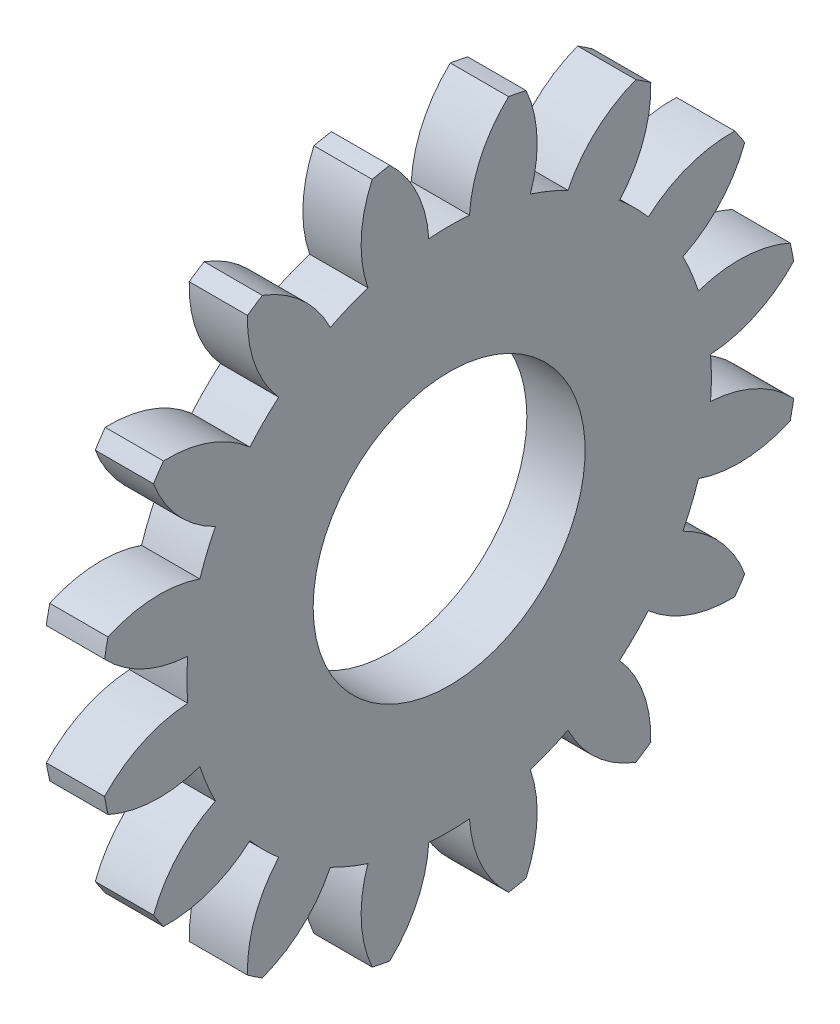
SolidWorks part; units mm, degrees
material "Zinc AC41A Alloy, As Cast"
ref_plane "Plane1" through (0, 0, 0) normal (0, 0, 1) x (1, 0, 0)
ref_plane "Plane2" through (0, 0, 0) normal (0, 1, 0) x (1, 0, 0)
ref_plane "Plane3" through (0, 0, 0) normal (1, 0, 0) x (0, 0, -1)
sketch "HoldingSke" plane through (0, 0, 0) normal (0, 1, 0) x (1, 0, 0)
  line L0 (0, 0) -> (0.9613, -0.2756)
  line L1 (-15, 0) -> (100, 0) construction
  line L2 (0, 0) -> (-2.1039, 2.3779)
  line L3 (0, 0) -> (-11.863, 4.5341)
  line L4 (0, 0) -> (8.3015, 2.3804)
  line L5 (0, 0) -> (-46.8476, -17.4728)
  line L6 (0, 0) -> (-1.2434, -0.839)
  line L7 (-2.1039, 2.3779) -> (8.6586, 51.2059)
  line L8 (-76.2, 54.61) -> (-75.2, 54.61)
  line L9 (-71.009, 38.7566) -> (-53.1078, 45.2721)
  line L10 (-76.2, 71.12) -> (104.1128, 71.12)
  line L11 (0, 0) -> (-1.5, 0)
  line L12 (-76.2, 101.6) -> (-76.162, 101.6)
  line L13 (24.9733, 27.94) -> (52.9518, 28.4284)
  line L14 (24.9733, 27.94) -> (24.9743, 27.94)
  line L15 (24.9733, 27.94) -> (100.4006, 29.5858)
  line L16 (-63.627, -1) -> (-12.827, -1)
  circle A0 centre (0, 0) radius 3.5
  circle A1 centre (0, 0) radius 6.749
  circle A2 centre (0, 0) radius 37.5
  circle A3 centre (0, 0) radius 3.5
  dimension "MHD" = 13.498
  dimension "Hub_dia" = 75
  dimension "Bore" = 7
  dimension "MBD" = 7
  dimension "Num_teeth" = 16
  dimension "Pitch" = 1
  dimension "Overall_len" = 50
  dimension "Show_teeth" = 16
  dimension "Thickness" = 1.5
  dimension "OAL" = 50.0001
  dimension "T_dim" = 1
  dimension "Ap" = 20
  dimension "H" = 19.05
  dimension "Pitch_radius" = 180.3128
  dimension "Width" = 1.5
  dimension "Backlash" = 0.038
  dimension "Addendum_fac" = 1
  dimension "Dedendum_fac" = 1.25
  dimension "Clearance_fac" = 0.25
  dimension "Dedendum_add" = 0.001
  dimension "Module" = 1
sketch "BasProSke" plane through (0, 0, 0) normal (0, 1, 0) x (1, 0, 0)
  line L0 (-10, 0) -> (60, 0) construction
  line L1 (0, 0) -> (0, 9)
  line L2 (0, 0) -> (1.5, 0)
  line L3 (1.5, 0) -> (1.5, 9)
  line L4 (1.5, 9) -> (0, 9)
  dimension "Thickness" = 1.5
  dimension "Diameter" = 18
revolve "Base-Revolve" add sketch "BasProSke" angle 360 about L0
sketch "TooCutSke" plane through (0, 0, 0) normal (1, 0, 0) x (0, 0, -1)
  line L1 (0, 0) -> (0, 107) construction
  line L2 (0, 0) -> (-0.8506, 7.9547) construction
  line L3 (0, 0) -> (-3.1089, 15.6293) construction
  line L4 (-0.8506, 7.9547) -> (-1.5544, 7.8146) construction
  arc A0 (0.5238, 6.7286) -> (-0.5238, 6.7286) centre (0, 0) ccw
  arc A1 (1.5534, 8.8907) -> (-1.5534, 8.8907) centre (0, 0) ccw
  circle A2 centre (0, 0) radius 8 construction
  circle A3 centre (0, 0) radius 7.5175 construction
  arc A4 (-0.5238, 6.7286) -> (-1.5534, 8.8907) centre (-3.7179, 6.5338) ccw
  arc A5 (1.5534, 8.8907) -> (0.5238, 6.7286) centre (3.7179, 6.5338) ccw
  dimension "Root_dia" = 13.498
  dimension "Overcut_dia" = 18.0508
  dimension "Pitch_dia" = 16
  dimension "Base_dia" = 15.0351
  dimension "Flank_rad" = 3.2
  dimension "Half_ang" = 11.25
  dimension "Half_CT" = 0.7176
extrude "ToothCut" cut sketch "TooCutSke" along normal through all
fillet "Breaks" [suppressed] radius 0.02
fillet "RootFillets" [suppressed] radius 0.251
pattern_circular "TeethCuts" count 16 every 22.5 about axis through (-10, 0, 0) along (1, 0, 0) of "ToothCut", "RootFillets", "Breaks"
sketch "HubNeaOneSke" plane through (0, 0, 0) normal (-1, 0, 0) x (0, 0, 1)
  circle A0 centre (0, 0) radius 6.749
  dimension "Diameter" = 13.498
extrude "HubNearOne" [suppressed] add sketch "HubNeaOneSke" along normal blind 48.5001
sketch "HubNeaBotSke" plane through (0, 0, 0) normal (-1, 0, 0) x (0, 0, 1)
  circle A0 centre (0, 0) radius 6.749
  dimension "Diameter" = 13.498
extrude "HubNearBoth" [suppressed] add sketch "HubNeaBotSke" along normal blind 24.25
ref_plane "FarPln" through (1.5, 0, 0) normal (1, 0, 0) x (0, 0, -1)
sketch "HubFarSke" plane through (1.5, 0, 0) normal (1, 0, 0) x (0, 0, -1)
  circle A0 centre (0, 0) radius 6.749
  dimension "Diameter" = 13.498
extrude "HubFar" [suppressed] add sketch "HubFarSke" along normal blind 24.25
sketch "BorSke" plane through (0, 0, 0) normal (1, 0, 0) x (0, 0, -1)
  circle A0 centre (0, 0) radius 3.5
  dimension "Diameter" = 7
extrude "Bore" cut sketch "BorSke" along normal mid plane 100.0001
sketch "KeySke" plane through (0, 0, 0) normal (1, 0, 0) x (0, 0, -1)
  line L0 (-1, 0) -> (-1, 4.5)
  line L1 (-1, 4.5) -> (1, 4.5)
  line L2 (1, 4.5) -> (1, 0)
  line L3 (0, 0) -> (0, 34) construction
  line L4 (-1, 0) -> (1, 0)
  dimension "Offset" = 4.5
  dimension "Width" = 2
extrude "Keyway" [suppressed] cut sketch "KeySke" along normal mid plane 100.0001
pattern_circular "Keyway2" [suppressed] count 2 every 90 about axis through (-10, 0, 0) along (1, 0, 0)
equation "' \"Module@HoldingSke\" = 6.35"
equation "' \"Num_teeth@HoldingSke\" = 12"
equation "' \"Ap@HoldingSke\" =  20"
equation "' \"Ap@HoldingSke\" = 20"
equation "' \"Width@HoldingSke\" = 0.5 * 25.4"
equation "' \"Hub_dia@HoldingSke\"= 1 * 25.4"
equation "' \"Hub_dia@HoldingSke\" = 1 * 25.4"
equation "' \"Overall_len@HoldingSke\" = 1.0 * 25.4"
equation "' \"Bore@HoldingSke\" = 0.75 * 25.4"
equation "' \"T_dim@HoldingSke\" = 0.1 * 25.4"
equation "' \"Width@KeySke\" = 0.25 * 25.4"
equation "' \"Show_teeth@HoldingSke\" = 13"
equation "' \"Backlash@HoldingSke\" = 0.009 * 25.4"
equation "' \"Addendum_fac@HoldingSke\" = 1.0"
equation "' \"Dedendum_fac@HoldingSke\" = 1.25"
equation "' \"Dedendum_add@HoldingSke\" = 0.00005 * 25.4"
equation "' \"Clearance_fac@HoldingSke\" = 0.25"
equation "\"Pitch@HoldingSke\" = 1 / \"Module@HoldingSke\""
equation "\"Overcut_dia@TooCutSke\" = (\"Num_teeth@HoldingSke\" + 2 * \"Addendum_fac@HoldingSke\") / \"Pitch@HoldingSke\" + 0.002 * 25.4"
equation "\"Pitch_dia@TooCutSke\" = \"Num_teeth@HoldingSke\" / \"Pitch@HoldingSke\""
equation "\"Base_dia@TooCutSke\" = \"Num_teeth@HoldingSke\" / \"Pitch@HoldingSke\" * cos((\"Ap@HoldingSke\"  * 3.14159265 / 180))"
equation "\"Root_dia@TooCutSke\" = (\"Num_teeth@HoldingSke\" + 2) / \"Pitch@HoldingSke\" - 2 * (\"Addendum_fac@HoldingSke\" + \"Dedendum_fac@HoldingSke\") / \"Pitch@HoldingSke\" - \"Dedendum_add@HoldingSke\" * 2"
equation "\"Half_ang@TooCutSke\" = 180 / \"Num_teeth@HoldingSke\""
equation "\"Half_CT@TooCutSke\" = \"Num_teeth@HoldingSke\" / \"Pitch@HoldingSke\" * sin((3.14159265 / 2 / \"Num_teeth@HoldingSke\")) / 2 - 7 * \"Backlash@HoldingSke\" / 4"
equation "\"Flank_rad@TooCutSke\" = \"Num_teeth@HoldingSke\" / \"Pitch@HoldingSke\" / 5"
equation "\"Radius@RootFillets\" = \"Clearance_fac@HoldingSke\" / \"Pitch@HoldingSke\" + \"Dedendum_add@HoldingSke\""
equation "\"Break_rad@Breaks\" = 0.02 / \"Pitch@HoldingSke\""
equation "\"Thickness@HoldingSke\" = \"Width@HoldingSke\""
equation "\"OAL@HoldingSke\" = \"Thickness@HoldingSke\""
equation "\"MHD@HoldingSke\" = (\"Num_teeth@HoldingSke\" + 2) / \"Pitch@HoldingSke\" - 2 * (\"Addendum_fac@HoldingSke\" + \"Dedendum_fac@HoldingSke\")  / \"Pitch@HoldingSke\" - \"Dedendum_add@HoldingSke\" * 2"
equation "\"MBD@HoldingSke\" = (\"Num_teeth@HoldingSke\" + 2) / \"Pitch@HoldingSke\" - 2 * (\"Addendum_fac@HoldingSke\" + \"Dedendum_fac@HoldingSke\")  / \"Pitch@HoldingSke\" - \"Dedendum_add@HoldingSke\" * 2 - 0.002 * 25.4"
equation "\"MHD@HoldingSke\" = ((sgn( \"MHD@HoldingSke\" - \"Hub_dia@HoldingSke\" )-1)*( \"MHD@HoldingSke\" - \"Hub_dia@HoldingSke\" ))/-2+ \"Hub_dia@HoldingSke\""
equation "\"MBD@HoldingSke\" = ((sgn( \"MBD@HoldingSke\" - \"Bore@HoldingSke\" )-1)*( \"MBD@HoldingSke\" - \"Bore@HoldingSke\" ))/-2+ \"Bore@HoldingSke\""
equation "\"OAL@HoldingSke\" = ((sgn( \"OAL@HoldingSke\" - \"Overall_len@HoldingSke\" )+1)*( \"OAL@HoldingSke\" - \"Overall_len@HoldingSke\" ))/2 + \"Overall_len@HoldingSke\" + 0.000002 * 25.4"
equation "\"Num_teeth@TeethCuts\" = int( \"Show_teeth@HoldingSke\" ) + 1"
equation "\"Num_teeth@TeethCuts\" = ((sgn( \"Num_teeth@TeethCuts\" - \"Num_teeth@HoldingSke\" )-1)*( \"Num_teeth@TeethCuts\" - \"Num_teeth@HoldingSke\" ))/-2+ \"Num_teeth@HoldingSke\""
equation "\"Num_teeth@TeethCuts\" = ((sgn( \"Num_teeth@TeethCuts\" - 2.0)+1)*( \"Num_teeth@TeethCuts\" - 2.0))/2 +2.0"
equation "\"Angle@TeethCuts\" = 360.0 / \"Num_teeth@HoldingSke\""
equation "\"Diameter@BasProSke\" = (\"Num_teeth@HoldingSke\" + 2 * \"Addendum_fac@HoldingSke\") / \"Pitch@HoldingSke\""
equation "\"Thickness@BasProSke\"  = \"Thickness@HoldingSke\""
equation "' \"Fillet_rad@BasProSke\" =  \"Thickness@HoldingSke\" * 0.05"
equation "' \"Fillet_rad@BasProSke\" = \"Thickness@HoldingSke\" * 0.05"
equation "\"MHD@HoldingSke\" = ((sgn( \"MHD@HoldingSke\" - \"Root_dia@TooCutSke\" )-1)*( \"MHD@HoldingSke\" - \"Root_dia@TooCutSke\" ))/-2+ \"Root_dia@TooCutSke\""
equation "\"Diameter@HubNeaOneSke\" = \"MHD@HoldingSke\""
equation "\"Length@HubNearOne\" = \"OAL@HoldingSke\" - \"Thickness@BasProSke\""
equation "\"Diameter@HubNeaBotSke\" = \"MHD@HoldingSke\""
equation "\"Length@HubNearBoth\" = ( \"OAL@HoldingSke\" - \"Thickness@BasProSke\" ) / 2.0"
equation "\"Thickness@FarPln\" = \"Thickness@BasProSke\""
equation "\"Diameter@HubFarSke\" = \"MHD@HoldingSke\""
equation "\"Length@HubFar\" = ( \"OAL@HoldingSke\" - \"Thickness@BasProSke\" ) / 2.0"
equation "\"Diameter@BorSke\" = \"MBD@HoldingSke\""
equation "\"D1@Bore\" = \"OAL@HoldingSke\" * 2.0"
equation "\"D1@Keyway\" = \"OAL@HoldingSke\" * 2.0"
equation "\"Offset@KeySke\" = \"T_dim@HoldingSke\" + \"MBD@HoldingSke\" / 2.0"
